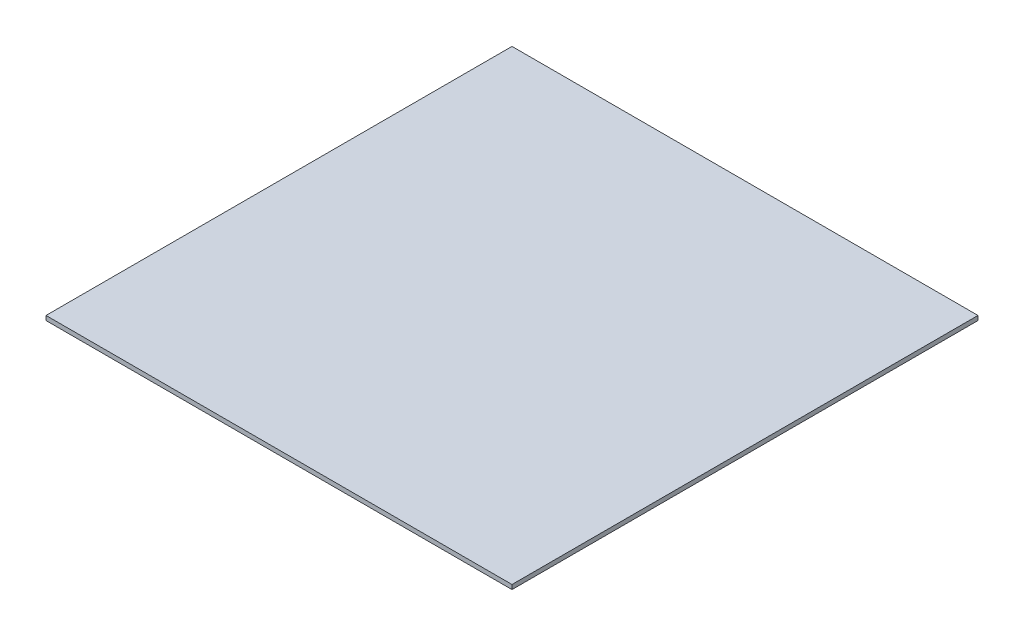
SolidWorks part; units mm, degrees
ref_plane "Plan de face" through (0, 0, 0) normal (0, 0, 1) x (1, 0, 0)
ref_plane "Plan de dessus" through (0, 0, 0) normal (0, 1, 0) x (1, 0, 0)
ref_plane "Plan de droite" through (0, 0, 0) normal (1, 0, 0) x (0, 0, -1)
sketch "Esquisse1" plane through (0, 0, 0) normal (0, 1, 0) x (1, 0, 0)
  line L1 (-105, 105) -> (105, 105)
  line L2 (-105, 105) -> (-105, -105)
  line L3 (-105, -105) -> (105, -105)
  line L4 (105, 105) -> (105, -105)
  line L5 (-105, 105) -> (105, -105) construction
  line L6 (-105, -105) -> (105, 105) construction
  point P0 (0, 0)
  dimension "D1" = 210
extrude "Boss.-Extru.1" add sketch "Esquisse1" along normal blind 2
